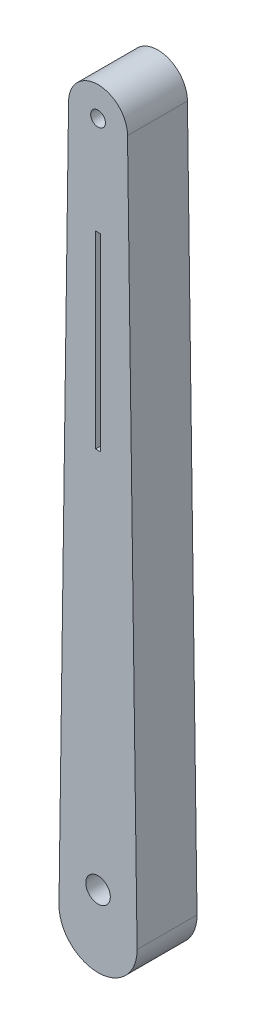
SolidWorks part; units mm, degrees
ref_plane "Front Plane" through (0, 0, 0) normal (0, 0, 1) x (1, 0, 0)
ref_plane "Top Plane" through (0, 0, 0) normal (0, 1, 0) x (1, 0, 0)
ref_plane "Right Plane" through (0, 0, 0) normal (1, 0, 0) x (0, 0, -1)
sketch "Sketch2" plane through (0, 0, 0) normal (0, 0, 1) x (1, 0, 0)
  line L0 (0, -72) -> (0, 74) construction
  line L1 (-8, -72) -> (-6, 74)
  line L2 (8, -72) -> (6, 74)
  arc A0 (-8, -72) -> (8, -72) centre (0, -72) ccw
  circle A3 centre (0, 74) radius 1.5
  circle A4 centre (0, -62) radius 2.5
  arc A5 (6, 74) -> (-6, 74) centre (0, 74) ccw
  point P3 (0, 0)
  point P8 (0, 80)
  point P9 (0, -80)
  dimension "D1" = 8
  dimension "D3" = 5
  dimension "D2" = 3
  dimension "D5" = 6
  dimension "D4" = 160
  dimension "D6" = 18
extrude "Boss-Extrude1" add sketch "Sketch2" along normal blind 12.2
sketch "Sketch3" plane through (0, 0, 12.2) normal (0, 0, 1) x (1, 0, 0)
  line L0 (-6, 74) -> (-8, -72) construction
  line L1 (8, -72) -> (6, 74) construction
  arc A1 (-7.9526, -68.5424) -> (7.9526, -68.5424) centre (0, -68.6513) ccw
extrude "Cut-Extrude-Thin2" cut sketch "Sketch3" against normal blind 60 and the other way through all flip side to cut thin
sketch "Sketch4" plane through (0, 0, 12.2) normal (0, 0, 1) x (1, 0, 0)
  line L0 (0, 53.9384) -> (0, 15.5002)
extrude "Cut-Extrude-Thin3" cut sketch "Sketch4" against normal blind 10 and the other way through all thin thin type mid plane wall 1
